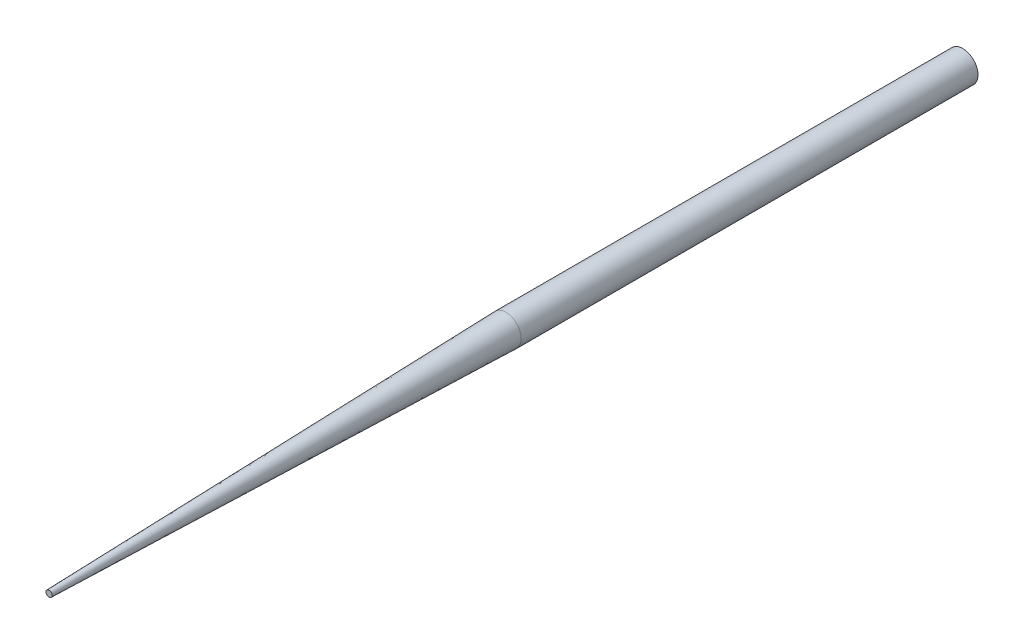
SolidWorks part; units mm, degrees
ref_plane "Plan de face" through (0, 0, 0) normal (0, 0, 1) x (1, 0, 0)
ref_plane "Plan de dessus" through (0, 0, 0) normal (0, 1, 0) x (1, 0, 0)
ref_plane "Plan de droite" through (0, 0, 0) normal (1, 0, 0) x (0, 0, -1)
sketch "Esquisse1" plane through (0, 0, 0) normal (0, 0, 1) x (1, 0, 0)
  circle A0 centre (0, 0) radius 0.5
  dimension "D1" = 1
extrude "Boss.-Extru.1" add sketch "Esquisse1" along normal blind 30
chamfer "Chanfrein1" distance 15 distance2 0.4 1 edges at (0.5, 0, 30)
